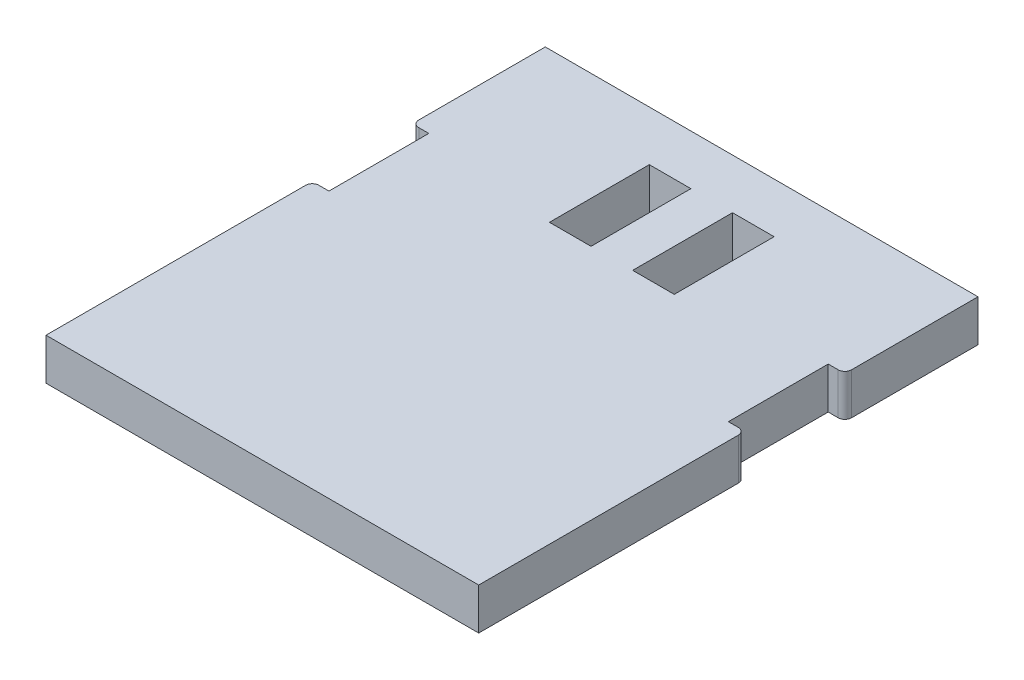
SolidWorks part; units mm, degrees
ref_plane "Front Plane" through (0, 0, 0) normal (0, 0, 1) x (1, 0, 0)
ref_plane "Top Plane" through (0, 0, 0) normal (0, 1, 0) x (1, 0, 0)
ref_plane "Right Plane" through (0, 0, 0) normal (1, 0, 0) x (0, 0, -1)
sketch "Sketch1" plane through (0, 0, 0) normal (0, 1, 0) x (1, 0, 0)
  line L1 (0, 0) -> (33.02, 0)
  line L2 (0, 0) -> (0, 38.1)
  line L3 (0, 38.1) -> (33.02, 38.1)
  line L4 (33.02, 0) -> (33.02, 38.1)
  line L5 (11.7475, 34.29) -> (14.9225, 34.29)
  line L6 (11.7475, 34.29) -> (11.7475, 26.67)
  line L7 (11.7475, 26.67) -> (14.9225, 26.67)
  line L8 (14.9225, 34.29) -> (14.9225, 26.67)
  line L9 (18.0975, 34.29) -> (21.2725, 34.29)
  line L10 (18.0975, 34.29) -> (18.0975, 26.67)
  line L11 (18.0975, 26.67) -> (21.2725, 26.67)
  line L12 (21.2725, 34.29) -> (21.2725, 26.67)
  point P9 (11.7475, 30.48)
  dimension "D1" = 33.02
  dimension "D2" = 38.1
  dimension "D3" = 7.62
  dimension "D4" = 3.175
  dimension "D5" = 11.7475
  dimension "D6" = 3.81
  dimension "D7" = 7.62
  dimension "D8" = 3.175
  dimension "D9" = 3.81
  dimension "D10" = 11.7475
extrude "Boss-Extrude1" add sketch "Sketch1" along normal blind 3.175
sketch "Sketch5" plane through (0, 0, 0) normal (0, -1, 0) x (1, 0, 0)
  line L0 (33.02, 0) -> (33.02, -38.1) construction
  line L1 (33.02, -20.32) -> (31.75, -20.32)
  line L2 (33.02, -20.32) -> (33.02, -27.94)
  line L3 (33.02, -27.94) -> (31.75, -27.94)
  line L4 (31.75, -20.32) -> (31.75, -27.94)
  line L5 (0, 0) -> (33.02, 0) construction
  line L6 (0, -38.1) -> (0, 0) construction
  line L7 (0, -20.32) -> (1.27, -20.32)
  line L8 (0, -20.32) -> (0, -27.94)
  line L9 (0, -27.94) -> (1.27, -27.94)
  line L10 (1.27, -20.32) -> (1.27, -27.94)
  dimension "D1" = 1.27
  dimension "D2" = 7.62
  dimension "D3" = 20.32
  dimension "D4" = 1.27
  dimension "D5" = 7.62
  dimension "D6" = 20.32
extrude "Cut-Extrude3" cut sketch "Sketch5" against normal through all
fillet "Fillet2" radius 0.508 4 edges at (33.02, 1.5875, -27.94) (33.02, 1.5875, -20.32) (0, 1.5875, -27.94) (0, 1.5875, -20.32)
